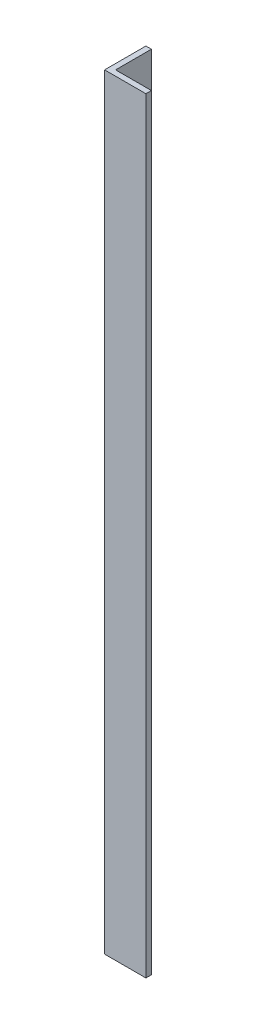
SolidWorks part; units mm, degrees
ref_plane "Ebene vorne" through (0, 0, 0) normal (0, 0, 1) x (1, 0, 0)
ref_plane "Ebene oben" through (0, 0, 0) normal (0, 1, 0) x (1, 0, 0)
ref_plane "Ebene rechts" through (0, 0, 0) normal (1, 0, 0) x (0, 0, -1)
sketch "Skizze1" plane through (0, 0, 0) normal (0, 1, 0) x (1, 0, 0)
  line L0 (0, 0) -> (15, 0)
  line L1 (15, 0) -> (15, 2)
  line L2 (15, 2) -> (2, 2)
  line L3 (2, 2) -> (2, 15)
  line L4 (2, 15) -> (0, 15)
  line L5 (0, 15) -> (0, 0)
  dimension "D1" = 15
  dimension "D2" = 2
extrude "Aufsatz-Linear austragen1" add sketch "Skizze1" along normal blind 278
